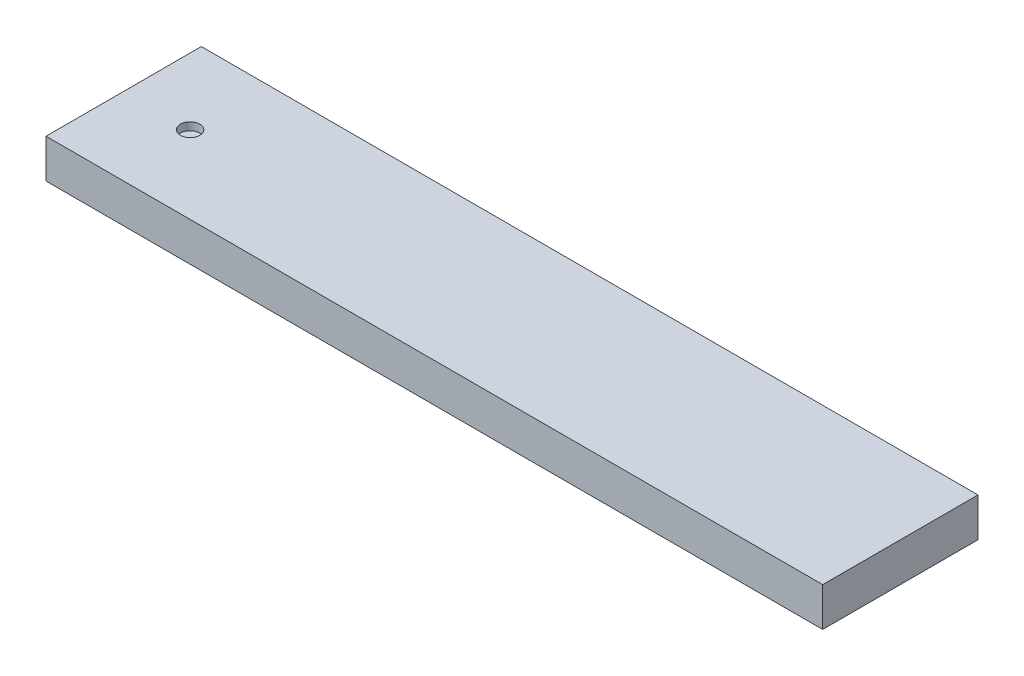
SolidWorks part; units mm, degrees
ref_plane "Front Plane" through (0, 0, 0) normal (0, 0, 1) x (1, 0, 0)
ref_plane "Top Plane" through (0, 0, 0) normal (0, 1, 0) x (1, 0, 0)
ref_plane "Right Plane" through (0, 0, 0) normal (1, 0, 0) x (0, 0, -1)
sketch "Sketch1" plane through (0, 0, 0) normal (0, 1, 0) x (1, 0, 0)
  line L1 (-127, -25.4) -> (127, -25.4)
  line L2 (-127, -25.4) -> (-127, 25.4)
  line L3 (-127, 25.4) -> (127, 25.4)
  line L4 (127, -25.4) -> (127, 25.4)
  line L5 (-127, -25.4) -> (127, 25.4) construction
  line L6 (-127, 25.4) -> (127, -25.4) construction
  point P0 (0, 0)
  dimension "D1" = 254
  dimension "D2" = 50.8
extrude "Boss-Extrude1" add sketch "Sketch1" along normal blind 12.7
sketch "Sketch2" plane through (0, 12.7, 0) normal (0, 1, 0) x (1, 0, 0)
  line L0 (-127, 0) -> (-105.2706, 0) construction
  line L1 (-127, 25.4) -> (-127, -25.4) construction
  circle A0 centre (-105.2706, 0) radius 3.175
  dimension "D1" = 6.35
extrude "Cut-Extrude1" cut sketch "Sketch2" against normal blind 2.54
